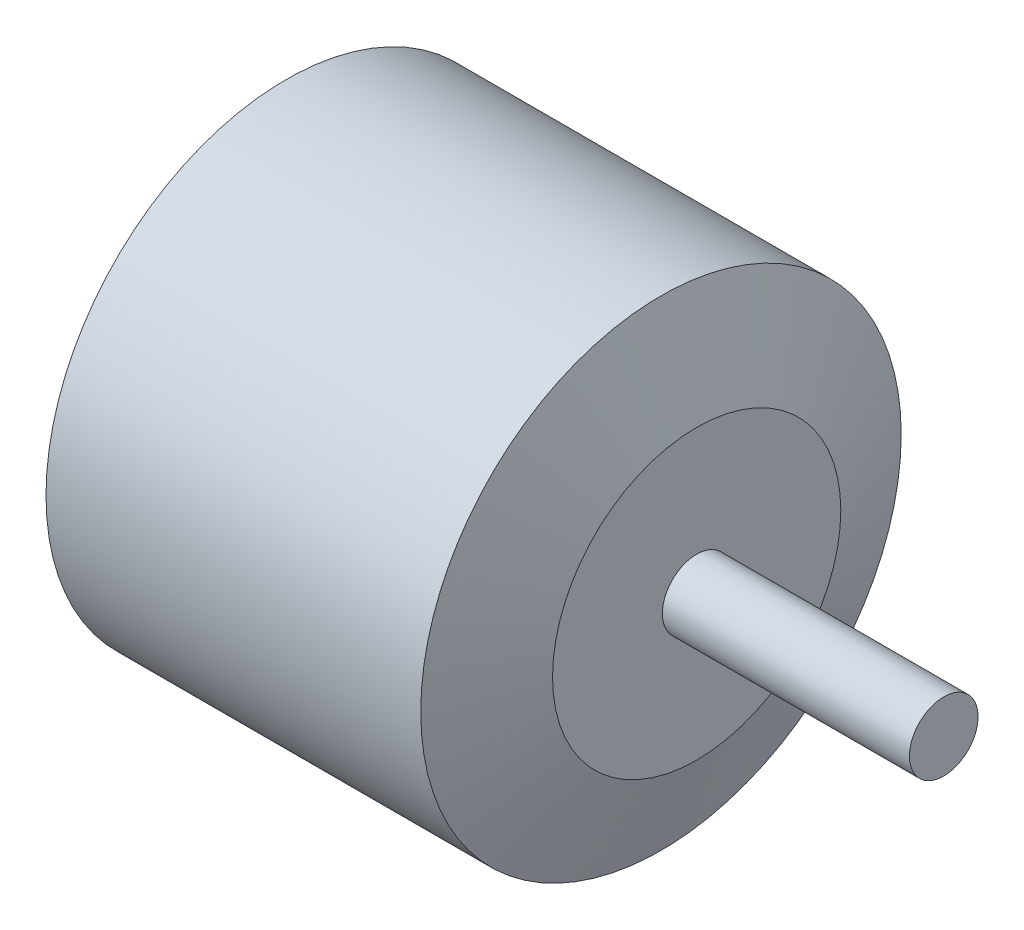
SolidWorks part; units mm, degrees
ref_plane "Front Plane" through (0, 0, 0) normal (0, 0, 1) x (1, 0, 0)
ref_plane "Top Plane" through (0, 0, 0) normal (0, 1, 0) x (1, 0, 0)
ref_plane "Right Plane" through (0, 0, 0) normal (1, 0, 0) x (0, 0, -1)
sketch "Sketch1" plane through (0, 0, 0) normal (0, 0, 1) x (1, 0, 0)
  line L0 (0, 0) -> (0, 2.5)
  line L1 (0, 2.5) -> (-18, 2.5)
  line L2 (-18, 2.5) -> (-18, 10.5)
  line L3 (-18, 10.5) -> (-20.6, 17.5)
  line L4 (-20.6, 17.5) -> (-47.9, 17.5)
  line L5 (-47.9, 17.5) -> (-50.5, 10.5)
  line L6 (-50.5, 10.5) -> (-50.5, 5.5)
  line L7 (-50.5, 5.5) -> (-53, 5.5)
  line L8 (-53, 5.5) -> (-53, 0)
  line L9 (-53, 0) -> (0, 0)
  dimension "D1" = 53
  dimension "D2" = 2.5
  dimension "D3" = 35
  dimension "D4" = 17.5
  dimension "D5" = 7
  dimension "D6" = 2.6
  dimension "D7" = 5.5
  dimension "D8" = 2.5
revolve "Revolve1" add sketch "Sketch1" angle 360 about L9
